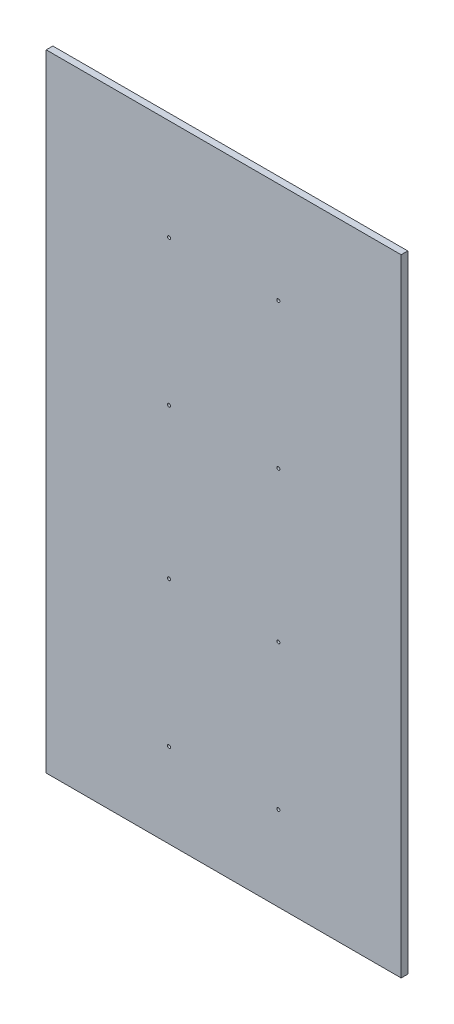
SolidWorks part; units mm, degrees
ref_plane "Front Plane" through (0, 0, 0) normal (0, 0, 1) x (1, 0, 0)
ref_plane "Top Plane" through (0, 0, 0) normal (0, 1, 0) x (1, 0, 0)
ref_plane "Right Plane" through (0, 0, 0) normal (1, 0, 0) x (0, 0, -1)
sketch "Sketch1" plane through (0, 0, 0) normal (0, 0, 1) x (1, 0, 0)
  line L1 (0, 0) -> (340, 0)
  line L2 (0, 0) -> (0, 600)
  line L3 (0, 600) -> (340, 600)
  line L4 (340, 0) -> (340, 600)
extrude "Sheet" add sketch "Sketch1" along normal blind 6.35
sketch "Sketch2" plane through (0, 0, 0) normal (0, 0, 1) x (1, 0, 0)
  circle A0 centre (222.35, 80.9) radius 1.5
  circle A1 centre (117.65, 80.9) radius 1.5
  circle A2 centre (222.35, 220.033) radius 1.5
  circle A3 centre (117.65, 220.033) radius 1.5
  circle A4 centre (222.35, 363.967) radius 1.5
  circle A5 centre (117.65, 363.967) radius 1.5
  circle A6 centre (222.35, 503.1) radius 1.5
  circle A7 centre (117.65, 503.1) radius 1.5
extrude "Holes" cut sketch "Sketch2" against normal through all and the other way through all
equation "\"t\" = 6.35mm"
equation "\"D1@Sheet\" = \"t\""
